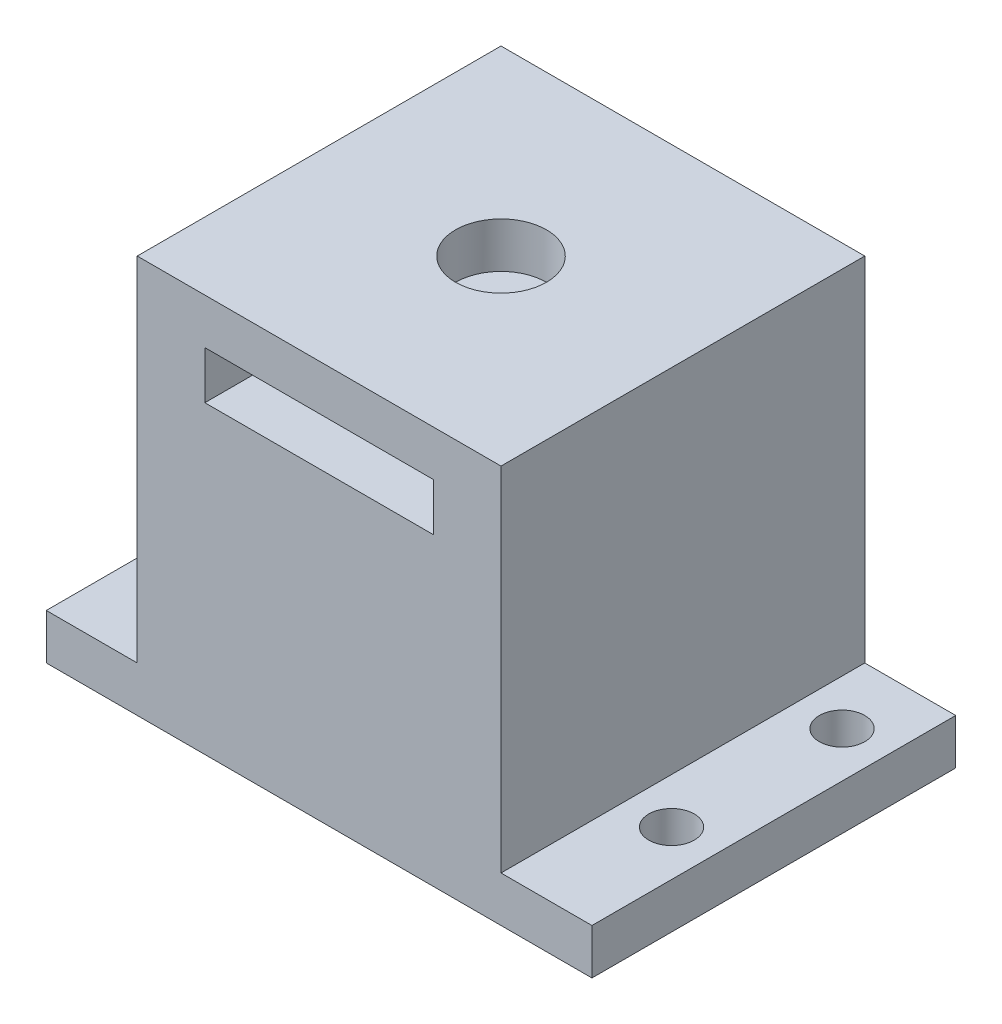
SolidWorks part; units mm, degrees
material "AISI 1020"
ref_plane "Front Plane" through (0, 0, 0) normal (0, 0, 1) x (1, 0, 0)
ref_plane "Top Plane" through (0, 0, 0) normal (0, 1, 0) x (1, 0, 0)
ref_plane "Right Plane" through (0, 0, 0) normal (1, 0, 0) x (0, 0, -1)
sketch "Sketch1" plane through (0, 0, 0) normal (0, 1, 0) x (1, 0, 0)
  line L1 (-16, -16) -> (16, -16)
  line L2 (-16, -16) -> (-16, 16)
  line L3 (-16, 16) -> (16, 16)
  line L4 (16, -16) -> (16, 16)
  line L5 (-16, -16) -> (16, 16) construction
  line L6 (-16, 16) -> (16, -16) construction
  point P0 (0, 0)
  dimension "D1" = 32
  dimension "D2" = 32
extrude "Boss-Extrude1" add sketch "Sketch1" along normal blind 35
sketch "Sketch2" plane through (0, 0, 0) normal (0, -1, 0) x (1, 0, 0)
  line L0 (-16, -16) -> (-16, 16) construction
  line L1 (-16, 16) -> (-24, 16)
  line L2 (-16, 16) -> (-16, -16)
  line L3 (-16, -16) -> (-24, -16)
  line L4 (-24, 16) -> (-24, -16)
  circle A0 centre (-20, 5) radius 2
  circle A1 centre (-20, -10) radius 2
  dimension "D2" = 4
  dimension "D3" = 20
  dimension "D4" = 15
  dimension "D5" = 6
  dimension "D1" = 8
extrude "Boss-Extrude2" add sketch "Sketch2" against normal blind 4
mirror "Mirror1" about plane through (0, 0, 0) normal (1, 0, 0) of "Boss-Extrude2"
sketch "Sketch4" plane through (0, 0, -16) normal (0, 0, -1) x (-1, 0, 0)
  line L0 (0, 35) -> (0, 26.6774) construction
  line L1 (-16, 35) -> (16, 35) construction
  line L3 (-10.05, 26.8) -> (10.05, 26.8)
  line L4 (-10.05, 26.8) -> (-10.05, 31)
  line L5 (-10.05, 31) -> (10.05, 31)
  line L6 (10.05, 26.8) -> (10.05, 31)
  point P9 (0, 31)
  dimension "D1" = 4.2
  dimension "D2" = 20.1
  dimension "D3" = 4
extrude "Cut-Extrude1" cut sketch "Sketch4" against normal up to next
sketch "Sketch5" plane through (0, 35, 0) normal (0, 1, 0) x (1, 0, 0)
  circle A0 centre (0, 0) radius 4
  dimension "D1" = 8
extrude "Cut-Extrude2" cut sketch "Sketch5" against normal up to next
